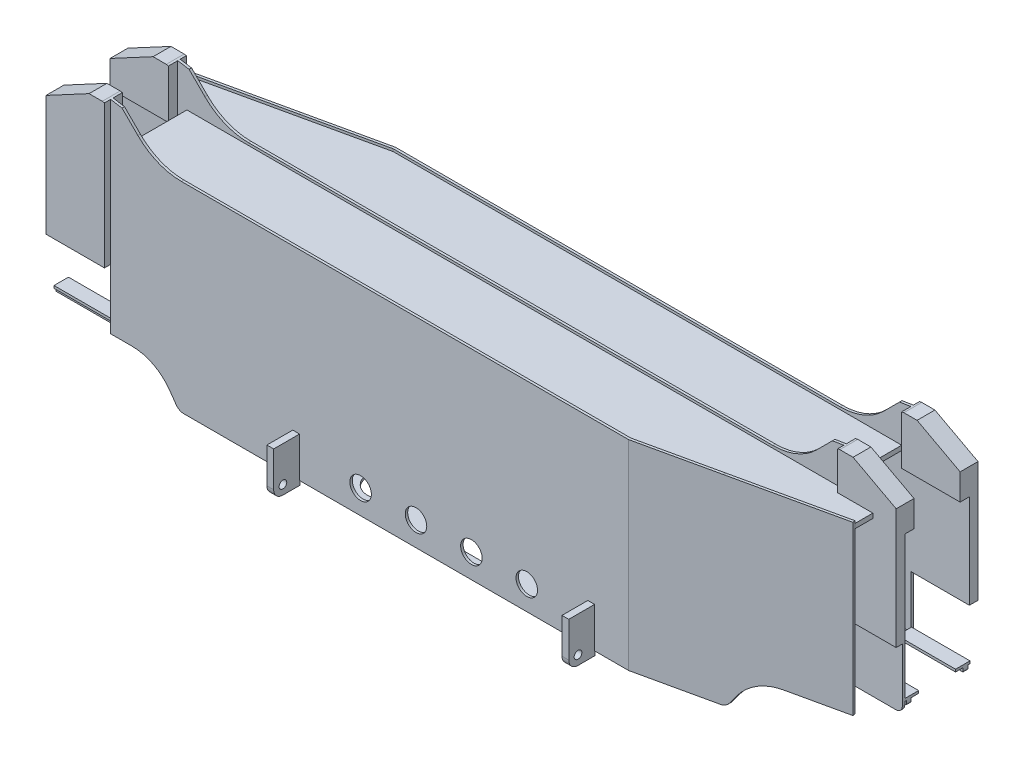
SolidWorks part; units mm, degrees
ref_plane "正面" through (0, 0, 0) normal (0, 0, 1) x (1, 0, 0)
ref_plane "平面" through (0, 0, 0) normal (0, 1, 0) x (1, 0, 0)
ref_plane "右側面" through (0, 0, 0) normal (1, 0, 0) x (0, 0, -1)
ref_plane "平面1" through (0, 0, 238) normal (0, 0, 1) x (1, 0, 0)
sketch "ｽｹｯﾁ2" plane through (0, 0, 238) normal (0, 0, 1) x (1, 0, 0)
  line L0 (20, 120) -> (259.781, 119.9998)
  line L1 (382.7741, 55.8641) -> (403.0452, 26.8271)
  line L2 (427.644, 13.9998) -> (2117.356, 13.9998)
  line L3 (2141.9548, 26.8271) -> (2162.2259, 55.8641)
  line L4 (2285.219, 119.9998) -> (2525, 120)
  line L5 (2545, 140) -> (2545, 315.36)
  line L6 (2545, 315.36) -> (2545, 706)
  line L7 (2545, 706) -> (2405, 781)
  line L8 (2405, 781) -> (2362, 781)
  line L9 (2362, 781) -> (2318, 774)
  line L10 (2318, 774) -> (2266.5789, 722.5791)
  line L11 (2125.157, 663.9999) -> (419.843, 663.9999)
  line L12 (278.4211, 722.5791) -> (227, 774)
  line L13 (227, 774) -> (183, 781)
  line L14 (183, 781) -> (140, 781)
  line L15 (140, 781) -> (0, 706)
  line L16 (0, 706) -> (0, 315.36)
  line L17 (0, 315.36) -> (0, 140)
  arc A0 (0, 140) -> (20, 120) centre (20, 140) ccw
  arc A1 (259.781, 119.9998) -> (382.7741, 55.8641) centre (259.781, -30) cw
  arc A2 (403.0452, 26.8271) -> (427.644, 13.9998) centre (427.644, 44) ccw
  arc A3 (2117.356, 13.9998) -> (2141.9548, 26.8271) centre (2117.356, 44) ccw
  arc A4 (2162.2259, 55.8641) -> (2285.219, 119.9998) centre (2285.219, -30) cw
  arc A5 (2525, 120) -> (2545, 140) centre (2525, 140) ccw
  arc A6 (2266.5789, 722.5791) -> (2125.157, 663.9999) centre (2125.157, 864) cw
  arc A7 (419.843, 663.9999) -> (278.4211, 722.5791) centre (419.843, 864) cw
extrude "ﾎﾞｽ - 押し出し1" add sketch "ｽｹｯﾁ2" along normal blind 8
sketch "ｽｹｯﾁ3" plane through (0, 0, 238) normal (0, 0, 1) x (1, 0, 0)
  line L0 (1072.5, 297) -> (1472.5, 297)
  line L1 (1472.5, 497) -> (1072.5, 497)
  circle A0 centre (972.5, 92) radius 35
  circle A1 centre (1272.5, 92) radius 35
  circle A2 centre (1572.5, 92) radius 35
  arc A3 (1472.5, 297) -> (1572.5, 397) centre (1472.5, 397) ccw
  arc A4 (1572.5, 397) -> (1472.5, 497) centre (1472.5, 397) ccw
  arc A5 (1072.5, 497) -> (972.5, 397) centre (1072.5, 397) ccw
  arc A6 (972.5, 397) -> (1072.5, 297) centre (1072.5, 397) ccw
  circle A7 centre (50, 499) radius 20.25
  circle A8 centre (2495, 499) radius 20.25
  circle A9 centre (27, 401.5) radius 10.5
  circle A10 centre (2518, 401.5) radius 10.5
sketch "ｽｹｯﾁ4" plane through (0, 0, 238) normal (0, 0, 1) x (1, 0, 0)
  line L0 (1072.5, 297) -> (1472.5, 297)
  line L1 (1472.5, 497) -> (1072.5, 497)
  circle A0 centre (972.5, 92) radius 35
  circle A1 centre (1272.5, 92) radius 35
  circle A2 centre (1572.5, 92) radius 35
  arc A3 (1472.5, 297) -> (1572.5, 397) centre (1472.5, 397) ccw
  arc A4 (1572.5, 397) -> (1472.5, 497) centre (1472.5, 397) ccw
  arc A5 (1072.5, 497) -> (972.5, 397) centre (1072.5, 397) ccw
  arc A6 (972.5, 397) -> (1072.5, 297) centre (1072.5, 397) ccw
  circle A7 centre (50, 499) radius 20.25
  circle A8 centre (2495, 499) radius 20.25
  circle A9 centre (27, 401.5) radius 10.5
  circle A10 centre (2518, 401.5) radius 10.5
extrude "ｶｯﾄ - 押し出し2" cut sketch "ｽｹｯﾁ4" along normal blind 8
ref_plane "平面2" through (0, 0, 20) normal (0, 0, 1) x (1, 0, 0)
sketch "ｽｹｯﾁ6" plane through (0, 0, 20) normal (0, 0, 1) x (1, 0, 0)
  line L0 (672.5, 14) -> (2117.356, 13.9998)
  line L1 (2141.9548, 26.8271) -> (2162.2259, 55.8641)
  line L2 (2285.219, 119.9998) -> (2355, 120)
  line L3 (2355, 120) -> (2355, 779.8864)
  line L4 (2355, 779.8864) -> (2318, 774)
  line L5 (2318, 774) -> (2266.5789, 722.5791)
  line L6 (2125.157, 663.9999) -> (672.5, 664)
  line L7 (672.5, 664) -> (672.5, 14)
  arc A0 (2117.356, 13.9998) -> (2141.9548, 26.8271) centre (2117.356, 44) ccw
  arc A1 (2162.2259, 55.8641) -> (2285.219, 119.9998) centre (2285.219, -30) cw
  arc A2 (2266.5789, 722.5791) -> (2125.157, 663.9999) centre (2125.157, 864) cw
extrude "ﾎﾞｽ - 押し出し2" add sketch "ｽｹｯﾁ6" along normal blind 8
sketch "ｽｹｯﾁ7" plane through (0, 0, 20) normal (0, 0, 1) x (1, 0, 0)
  circle A0 centre (1002.5, 92) radius 35
  circle A1 centre (1182.5, 92) radius 35
  circle A2 centre (1362.5, 92) radius 35
  circle A3 centre (1542.5, 92) radius 35
sketch "ｽｹｯﾁ8" plane through (0, 0, 20) normal (0, 0, 1) x (1, 0, 0)
  circle A0 centre (1002.5, 92) radius 35
  circle A1 centre (1182.5, 92) radius 35
  circle A2 centre (1362.5, 92) radius 35
  circle A3 centre (1542.5, 92) radius 35
extrude "ｶｯﾄ - 押し出し4" cut sketch "ｽｹｯﾁ8" along normal blind 8
ref_plane "平面3" through (0, 0, 456) normal (0, 0, 1) x (1, 0, 0)
sketch "ｽｹｯﾁ10" plane through (0, 0, 456) normal (0, 0, 1) x (1, 0, 0)
  line L0 (190, 120) -> (259.781, 119.9998)
  line L1 (382.7741, 55.8641) -> (403.0452, 26.8271)
  line L2 (427.644, 13.9998) -> (1872.5, 14)
  line L3 (1872.5, 14) -> (1872.5, 664)
  line L4 (1872.5, 664) -> (419.843, 663.9999)
  line L5 (278.4211, 722.5791) -> (227, 774)
  line L6 (227, 774) -> (190, 779.8864)
  line L7 (190, 779.8864) -> (190, 120)
  arc A0 (259.781, 119.9998) -> (382.7741, 55.8641) centre (259.781, -30) cw
  arc A1 (403.0452, 26.8271) -> (427.644, 13.9998) centre (427.644, 44) ccw
  arc A2 (419.843, 663.9999) -> (278.4211, 722.5791) centre (419.843, 864) cw
extrude "ﾎﾞｽ - 押し出し3" add sketch "ｽｹｯﾁ10" along normal blind 8
sketch "ｽｹｯﾁ11" plane through (0, 0, 456) normal (0, 0, 1) x (1, 0, 0)
  circle A0 centre (1002.5, 92) radius 35
  circle A1 centre (1182.5, 92) radius 35
  circle A2 centre (1362.5, 92) radius 35
  circle A3 centre (1542.5, 92) radius 35
sketch "ｽｹｯﾁ12" plane through (0, 0, 456) normal (0, 0, 1) x (1, 0, 0)
  circle A0 centre (1002.5, 92) radius 35
  circle A1 centre (1182.5, 92) radius 35
  circle A2 centre (1362.5, 92) radius 35
  circle A3 centre (1542.5, 92) radius 35
extrude "ｶｯﾄ - 押し出し6" cut sketch "ｽｹｯﾁ12" along normal blind 8
ref_plane "平面4" through (0, 14, 0) normal (0, 1, 0) x (1, 0, 0)
sketch "ｽｹｯﾁ14" plane through (0, 14, 0) normal (0, 1, 0) x (1, 0, 0)
  line L0 (678.3594, -26.7085) -> (75.7, -159.54)
  line L1 (75.7, -159.54) -> (73.9781, -151.7275)
  line L2 (73.9781, -151.7275) -> (671.6288, -20)
  line L3 (671.6288, -20) -> (676.8807, -20)
  line L4 (676.8807, -20) -> (678.3594, -26.7085)
extrude "ﾎﾞｽ - 押し出し4" add sketch "ｽｹｯﾁ14" along normal blind 650
sketch "ｽｹｯﾁ15" plane through (0, 14, 0) normal (0, 1, 0) x (1, 0, 0)
  line L0 (1866.6406, -457.2915) -> (2469.3, -324.46)
  line L1 (2469.3, -324.46) -> (2471.0219, -332.2725)
  line L2 (2471.0219, -332.2725) -> (1873.3712, -464)
  line L3 (1873.3712, -464) -> (1868.1193, -464)
  line L4 (1868.1193, -464) -> (1866.6406, -457.2915)
extrude "ﾎﾞｽ - 押し出し5" add sketch "ｽｹｯﾁ15" along normal blind 650
ref_plane "平面5" through (0, 641, 0) normal (0, 1, 0) x (1, 0, 0)
sketch "ｽｹｯﾁ17" plane through (0, 641, 0) normal (0, 1, 0) x (1, 0, 0)
  line L0 (2325, -28) -> (672.5, -28)
  line L1 (672.5, -28) -> (75.7, -159.54)
  line L2 (75.7, -159.54) -> (75.7, -238)
  line L3 (75.7, -238) -> (2325, -238)
  line L4 (2325, -238) -> (2325, -28)
extrude "ﾎﾞｽ - 押し出し6" add sketch "ｽｹｯﾁ17" along normal blind 15
sketch "ｽｹｯﾁ18" plane through (0, 641, 0) normal (0, 1, 0) x (1, 0, 0)
  line L0 (220, -246) -> (2469.3, -246)
  line L1 (2469.3, -246) -> (2469.3, -324.46)
  line L2 (2469.3, -324.46) -> (1872.5, -456)
  line L3 (1872.5, -456) -> (220, -456)
  line L4 (220, -456) -> (220, -246)
extrude "ﾎﾞｽ - 押し出し7" add sketch "ｽｹｯﾁ18" along normal blind 15
ref_plane "平面6" through (0, 22, 0) normal (0, 1, 0) x (1, 0, 0)
sketch "ｽｹｯﾁ20" plane through (0, 22, 0) normal (0, 1, 0) x (1, 0, 0)
  line L0 (804, -28) -> (2098.5, -28)
  line L1 (2098.5, -28) -> (2098.5, -238)
  line L2 (2098.5, -238) -> (804, -238)
  line L3 (804, -238) -> (804, -28)
extrude "ﾎﾞｽ - 押し出し8" add sketch "ｽｹｯﾁ20" along normal blind 8
sketch "ｽｹｯﾁ21" plane through (0, 22, 0) normal (0, 1, 0) x (1, 0, 0)
  line L0 (1202, -73) -> (1342, -73)
  line L1 (1342, -193) -> (1202, -193)
  circle A0 centre (972, -133) radius 60
  circle A1 centre (1572, -133) radius 60
  circle A2 centre (1942, -133) radius 60
  arc A3 (1342, -73) -> (1402, -133) centre (1342, -133) cw
  arc A4 (1402, -133) -> (1342, -193) centre (1342, -133) cw
  arc A5 (1202, -193) -> (1142, -133) centre (1202, -133) cw
  arc A6 (1142, -133) -> (1202, -73) centre (1202, -133) cw
sketch "ｽｹｯﾁ22" plane through (0, 22, 0) normal (0, 1, 0) x (1, 0, 0)
  line L0 (1202, -73) -> (1342, -73)
  line L1 (1342, -193) -> (1202, -193)
  circle A0 centre (972, -133) radius 60
  circle A1 centre (1572, -133) radius 60
  circle A2 centre (1942, -133) radius 60
  arc A3 (1342, -73) -> (1402, -133) centre (1342, -133) cw
  arc A4 (1402, -133) -> (1342, -193) centre (1342, -133) cw
  arc A5 (1202, -193) -> (1142, -133) centre (1202, -133) cw
  arc A6 (1142, -133) -> (1202, -73) centre (1202, -133) cw
extrude "ｶｯﾄ - 押し出し8" cut sketch "ｽｹｯﾁ22" along normal blind 8
sketch "ｽｹｯﾁ23" plane through (0, 22, 0) normal (0, 1, 0) x (1, 0, 0)
  line L0 (446.5, -246) -> (1741, -246)
  line L1 (1741, -246) -> (1741, -456)
  line L2 (1741, -456) -> (446.5, -456)
  line L3 (446.5, -456) -> (446.5, -246)
extrude "ﾎﾞｽ - 押し出し9" add sketch "ｽｹｯﾁ23" along normal blind 8
sketch "ｽｹｯﾁ24" plane through (0, 22, 0) normal (0, 1, 0) x (1, 0, 0)
  line L0 (1203, -291) -> (1343, -291)
  line L1 (1343, -411) -> (1203, -411)
  circle A0 centre (603, -351) radius 60
  circle A1 centre (973, -351) radius 60
  circle A2 centre (1573, -351) radius 60
  arc A3 (1343, -291) -> (1403, -351) centre (1343, -351) cw
  arc A4 (1403, -351) -> (1343, -411) centre (1343, -351) cw
  arc A5 (1203, -411) -> (1143, -351) centre (1203, -351) cw
  arc A6 (1143, -351) -> (1203, -291) centre (1203, -351) cw
extrude "ｶｯﾄ - 押し出し9" cut sketch "ｽｹｯﾁ24" along normal blind 8
ref_plane "平面7" through (0, 138, 0) normal (0, 1, 0) x (1, 0, 0)
sketch "ｽｹｯﾁ26" plane through (0, 138, 0) normal (0, 1, 0) x (1, 0, 0)
  line L0 (768, -28) -> (1712, -28)
  line L1 (1712, -28) -> (1712, -238)
  line L2 (1712, -238) -> (768, -238)
  line L3 (768, -238) -> (768, -28)
extrude "ﾎﾞｽ - 押し出し10" add sketch "ｽｹｯﾁ26" along normal blind 6
sketch "ｽｹｯﾁ27" plane through (0, 138, 0) normal (0, 1, 0) x (1, 0, 0)
  line L0 (833, -246) -> (1777, -246)
  line L1 (1777, -246) -> (1777, -456)
  line L2 (1777, -456) -> (833, -456)
  line L3 (833, -456) -> (833, -246)
extrude "ﾎﾞｽ - 押し出し11" add sketch "ｽｹｯﾁ27" along normal blind 6
ref_plane "平面8" through (0, 0, 218) normal (0, 0, 1) x (1, 0, 0)
sketch "ｽｹｯﾁ29" plane through (0, 0, 218) normal (0, 0, 1) x (1, 0, 0)
  line L0 (0, 315.36) -> (190, 315.36)
  line L1 (190, 315.36) -> (190, 779.8864)
  line L2 (190, 779.8864) -> (183, 781)
  line L3 (183, 781) -> (140, 781)
  line L4 (140, 781) -> (0, 706)
  line L5 (0, 706) -> (0, 315.36)
extrude "ﾎﾞｽ - 押し出し12" add sketch "ｽｹｯﾁ29" along normal blind 20
ref_plane "平面9" through (0, 0, 464) normal (0, 0, 1) x (1, 0, 0)
sketch "ｽｹｯﾁ31" plane through (0, 0, 464) normal (0, 0, 1) x (1, 0, 0)
  line L0 (0, 315.36) -> (190, 315.36)
  line L1 (190, 315.36) -> (190, 779.8864)
  line L2 (190, 779.8864) -> (183, 781)
  line L3 (183, 781) -> (140, 781)
  line L4 (140, 781) -> (0, 706)
  line L5 (0, 706) -> (0, 315.36)
extrude "ﾎﾞｽ - 押し出し13" add sketch "ｽｹｯﾁ31" along normal blind 20
sketch "ｽｹｯﾁ32" plane through (0, 0, 0) normal (0, 0, 1) x (1, 0, 0)
  line L0 (2545, 315.36) -> (2545, 706)
  line L1 (2545, 706) -> (2405, 781)
  line L2 (2405, 781) -> (2362, 781)
  line L3 (2362, 781) -> (2355, 779.8864)
  line L4 (2355, 779.8864) -> (2355, 315.36)
  line L5 (2355, 315.36) -> (2545, 315.36)
extrude "ﾎﾞｽ - 押し出し14" add sketch "ｽｹｯﾁ32" along normal blind 20
ref_plane "平面10" through (0, 0, 246) normal (0, 0, 1) x (1, 0, 0)
sketch "ｽｹｯﾁ34" plane through (0, 0, 246) normal (0, 0, 1) x (1, 0, 0)
  line L0 (2545, 315.36) -> (2545, 706)
  line L1 (2545, 706) -> (2405, 781)
  line L2 (2405, 781) -> (2362, 781)
  line L3 (2362, 781) -> (2355, 779.8864)
  line L4 (2355, 779.8864) -> (2355, 315.36)
  line L5 (2355, 315.36) -> (2545, 315.36)
extrude "ﾎﾞｽ - 押し出し15" add sketch "ｽｹｯﾁ34" along normal blind 20
sketch "ｽｹｯﾁ35" plane through (0, 0, 20) normal (0, 0, 1) x (1, 0, 0)
  line L0 (2545, 315.36) -> (2545, 706)
  line L1 (2545, 706) -> (2405, 781)
  line L2 (2405, 781) -> (2362, 781)
  line L3 (2362, 781) -> (2355, 779.8864)
  line L4 (2355, 779.8864) -> (2355, 315.36)
  line L5 (2355, 315.36) -> (2545, 315.36)
extrude "ﾎﾞｽ - 押し出し16" add sketch "ｽｹｯﾁ35" along normal blind 8
sketch "ｽｹｯﾁ36" plane through (0, 0, 456) normal (0, 0, 1) x (1, 0, 0)
  line L0 (0, 315.36) -> (190, 315.36)
  line L1 (190, 315.36) -> (190, 779.8864)
  line L2 (190, 779.8864) -> (183, 781)
  line L3 (183, 781) -> (140, 781)
  line L4 (140, 781) -> (0, 706)
  line L5 (0, 706) -> (0, 315.36)
extrude "ﾎﾞｽ - 押し出し17" add sketch "ｽｹｯﾁ36" along normal blind 8
sketch "ｽｹｯﾁ37" plane through (0, 0, 246) normal (0, 0, 1) x (1, 0, 0)
  line L0 (0, 620.82) -> (190, 620.82)
  line L1 (190, 620.82) -> (190, 779.8864)
  line L2 (190, 779.8864) -> (183, 781)
  line L3 (183, 781) -> (140, 781)
  line L4 (140, 781) -> (0, 706)
  line L5 (0, 706) -> (0, 620.82)
extrude "ﾎﾞｽ - 押し出し18" add sketch "ｽｹｯﾁ37" along normal blind 30
ref_plane "平面11" through (0, 0, 426) normal (0, 0, 1) x (1, 0, 0)
sketch "ｽｹｯﾁ39" plane through (0, 0, 426) normal (0, 0, 1) x (1, 0, 0)
  line L0 (0, 620.82) -> (190, 620.82)
  line L1 (190, 620.82) -> (190, 779.8864)
  line L2 (190, 779.8864) -> (183, 781)
  line L3 (183, 781) -> (140, 781)
  line L4 (140, 781) -> (0, 706)
  line L5 (0, 706) -> (0, 620.82)
extrude "ﾎﾞｽ - 押し出し19" add sketch "ｽｹｯﾁ39" along normal blind 30
ref_plane "平面12" through (0, 0, 28) normal (0, 0, 1) x (1, 0, 0)
sketch "ｽｹｯﾁ41" plane through (0, 0, 28) normal (0, 0, 1) x (1, 0, 0)
  line L0 (2545, 620.82) -> (2545, 706)
  line L1 (2545, 706) -> (2405, 781)
  line L2 (2405, 781) -> (2362, 781)
  line L3 (2362, 781) -> (2355, 779.8864)
  line L4 (2355, 779.8864) -> (2355, 620.82)
  line L5 (2355, 620.82) -> (2545, 620.82)
extrude "ﾎﾞｽ - 押し出し20" add sketch "ｽｹｯﾁ41" along normal blind 30
ref_plane "平面13" through (0, 0, 208) normal (0, 0, 1) x (1, 0, 0)
sketch "ｽｹｯﾁ43" plane through (0, 0, 208) normal (0, 0, 1) x (1, 0, 0)
  line L0 (2545, 620.82) -> (2545, 706)
  line L1 (2545, 706) -> (2405, 781)
  line L2 (2405, 781) -> (2362, 781)
  line L3 (2362, 781) -> (2355, 779.8864)
  line L4 (2355, 779.8864) -> (2355, 620.82)
  line L5 (2355, 620.82) -> (2545, 620.82)
extrude "ﾎﾞｽ - 押し出し21" add sketch "ｽｹｯﾁ43" along normal blind 30
sketch "ｽｹｯﾁ44" plane through (0, 138, 0) normal (0, 1, 0) x (1, 0, 0)
  line L0 (0, -251) -> (833, -251)
  line L1 (833, -251) -> (833, -451)
  line L2 (833, -451) -> (0, -451)
  line L3 (0, -451) -> (0, -251)
extrude "ﾎﾞｽ - 押し出し22" add sketch "ｽｹｯﾁ44" along normal blind 12
sketch "ｽｹｯﾁ45" plane through (0, 138, 0) normal (0, 1, 0) x (1, 0, 0)
  line L0 (-10, -267) -> (145.3, -267)
  line L1 (185.3, -307) -> (185.3, -395)
  line L2 (145.3, -435) -> (-10, -435)
  line L3 (-10, -435) -> (-10, -267)
  arc A0 (145.3, -267) -> (185.3, -307) centre (145.3, -307) cw
  arc A1 (185.3, -395) -> (145.3, -435) centre (145.3, -395) cw
sketch "ｽｹｯﾁ46" plane through (0, 138, 0) normal (0, 1, 0) x (1, 0, 0)
  line L0 (-10, -267) -> (145.3, -267)
  line L1 (185.3, -307) -> (185.3, -395)
  line L2 (145.3, -435) -> (-10, -435)
  line L3 (-10, -435) -> (-10, -267)
  arc A0 (145.3, -267) -> (185.3, -307) centre (145.3, -307) cw
  arc A1 (185.3, -395) -> (145.3, -435) centre (145.3, -395) cw
extrude "ｶｯﾄ - 押し出し11" cut sketch "ｽｹｯﾁ46" along normal blind 12
sketch "ｽｹｯﾁ47" plane through (0, 138, 0) normal (0, 1, 0) x (1, 0, 0)
  line L0 (1712, -33) -> (2545, -33)
  line L1 (2545, -33) -> (2545, -233)
  line L2 (2545, -233) -> (1712, -233)
  line L3 (1712, -233) -> (1712, -33)
extrude "ﾎﾞｽ - 押し出し23" add sketch "ｽｹｯﾁ47" along normal blind 12
sketch "ｽｹｯﾁ48" plane through (0, 138, 0) normal (0, 1, 0) x (1, 0, 0)
  line L0 (2555, -217) -> (2399.7, -217)
  line L1 (2359.7, -177) -> (2359.7, -89)
  line L2 (2399.7, -49) -> (2555, -49)
  line L3 (2555, -49) -> (2555, -217)
  arc A0 (2399.7, -217) -> (2359.7, -177) centre (2399.7, -177) cw
  arc A1 (2359.7, -89) -> (2399.7, -49) centre (2399.7, -89) cw
extrude "ｶｯﾄ - 押し出し12" cut sketch "ｽｹｯﾁ48" along normal blind 12
ref_plane "平面14" through (0, 150, 0) normal (0, 1, 0) x (1, 0, 0)
sketch "ｽｹｯﾁ50" plane through (0, 150, 0) normal (0, 1, 0) x (1, 0, 0)
  line L0 (0, -244) -> (190, -244)
  line L1 (190, -244) -> (190, -291)
  line L2 (190, -291) -> (0, -291)
  line L3 (0, -291) -> (0, -244)
  line L4 (0, -411) -> (190, -411)
  line L5 (190, -411) -> (190, -458)
  line L6 (190, -458) -> (0, -458)
  line L7 (0, -458) -> (0, -411)
  line L8 (215.708, -244) -> (833, -244)
  line L9 (833, -244) -> (833, -291)
  line L10 (833, -291) -> (215.708, -291)
  line L11 (215.708, -291) -> (215.708, -244)
  line L12 (215.708, -411) -> (833, -411)
  line L13 (833, -411) -> (833, -458)
  line L14 (833, -458) -> (215.708, -458)
  line L15 (215.708, -458) -> (215.708, -411)
extrude "ﾎﾞｽ - 押し出し24" add sketch "ｽｹｯﾁ50" along normal blind 8
sketch "ｽｹｯﾁ51" plane through (0, 150, 0) normal (0, 1, 0) x (1, 0, 0)
  line L0 (1712, -193) -> (2329.292, -193)
  line L1 (2329.292, -193) -> (2329.292, -240)
  line L2 (2329.292, -240) -> (1712, -240)
  line L3 (1712, -240) -> (1712, -193)
  line L4 (1712, -26) -> (2329.292, -26)
  line L5 (2329.292, -26) -> (2329.292, -73)
  line L6 (2329.292, -73) -> (1712, -73)
  line L7 (1712, -73) -> (1712, -26)
  line L8 (2355, -193) -> (2545, -193)
  line L9 (2545, -193) -> (2545, -240)
  line L10 (2545, -240) -> (2355, -240)
  line L11 (2355, -240) -> (2355, -193)
  line L12 (2355, -26) -> (2545, -26)
  line L13 (2545, -26) -> (2545, -73)
  line L14 (2545, -73) -> (2355, -73)
  line L15 (2355, -73) -> (2355, -26)
extrude "ﾎﾞｽ - 押し出し25" add sketch "ｽｹｯﾁ51" along normal blind 8
ref_plane "平面15" through (1771.5, 0, 0) normal (1, 0, 0) x (0, 0, -1)
sketch "ｽｹｯﾁ53" plane through (1771.5, 0, 0) normal (1, 0, 0) x (0, 0, -1)
  line L0 (-28, 30) -> (-40.32, 29.97)
  line L1 (-40.32, 29.97) -> (-63.75, 129.12)
  line L2 (-63.75, 129.12) -> (-53.54, 138)
  line L3 (-53.54, 138) -> (-28, 30)
extrude "ﾎﾞｽ - 押し出し27" add sketch "ｽｹｯﾁ53" along normal blind 319 separate body
sketch "ｽｹｯﾁ54" plane through (1771.5, 0, 0) normal (1, 0, 0) x (0, 0, -1)
  line L0 (-212.46, 138) -> (-202.25, 129.12)
  line L1 (-202.25, 129.12) -> (-225.68, 29.97)
  line L2 (-225.68, 29.97) -> (-238, 30)
  line L3 (-238, 30) -> (-212.46, 138)
extrude "ﾎﾞｽ - 押し出し29" add sketch "ｽｹｯﾁ54" along normal blind 319 separate body
ref_plane "平面16" through (454.5, 0, 0) normal (1, 0, 0) x (0, 0, -1)
sketch "ｽｹｯﾁ56" plane through (454.5, 0, 0) normal (1, 0, 0) x (0, 0, -1)
  line L0 (-430.46, 138) -> (-420.25, 129.12)
  line L1 (-420.25, 129.12) -> (-443.68, 29.97)
  line L2 (-443.68, 29.97) -> (-456, 30)
  line L3 (-456, 30) -> (-430.46, 138)
extrude "ﾎﾞｽ - 押し出し31" add sketch "ｽｹｯﾁ56" along normal blind 319 separate body
sketch "ｽｹｯﾁ57" plane through (454.5, 0, 0) normal (1, 0, 0) x (0, 0, -1)
  line L0 (-246, 30) -> (-258.32, 29.97)
  line L1 (-258.32, 29.97) -> (-281.75, 129.12)
  line L2 (-281.75, 129.12) -> (-271.54, 138)
  line L3 (-271.54, 138) -> (-246, 30)
extrude "ﾎﾞｽ - 押し出し33" add sketch "ｽｹｯﾁ57" along normal blind 319 separate body
sketch "ｽｹｯﾁ58" plane through (0, 0, 0) normal (0, 0, 1) x (1, 0, 0)
  line L0 (-80, -80) -> (2625, -80)
  line L1 (2625, -80) -> (2625, 860)
  line L2 (2625, 860) -> (-80, 860)
  line L3 (-80, 860) -> (-80, -80)
  line L4 (20, 120) -> (259.781, 119.9998)
  line L5 (382.7741, 55.8641) -> (403.0452, 26.8271)
  line L6 (427.644, 13.9998) -> (2117.356, 13.9998)
  line L7 (2141.9548, 26.8271) -> (2162.2259, 55.8641)
  line L8 (2285.219, 119.9998) -> (2525, 120)
  line L9 (2545, 140) -> (2545, 315.36)
  line L10 (2545, 315.36) -> (2545, 706)
  line L11 (2545, 706) -> (2405, 781)
  line L12 (2405, 781) -> (2362, 781)
  line L13 (2362, 781) -> (2318, 774)
  line L14 (2318, 774) -> (2266.5789, 722.5791)
  line L15 (2125.157, 663.9999) -> (419.843, 663.9999)
  line L16 (278.4211, 722.5791) -> (227, 774)
  line L17 (227, 774) -> (183, 781)
  line L18 (183, 781) -> (140, 781)
  line L19 (140, 781) -> (0, 706)
  line L20 (0, 706) -> (0, 315.36)
  line L21 (0, 315.36) -> (0, 140)
  arc A0 (0, 140) -> (20, 120) centre (20, 140) ccw
  arc A1 (259.781, 119.9998) -> (382.7741, 55.8641) centre (259.781, -30) cw
  arc A2 (403.0452, 26.8271) -> (427.644, 13.9998) centre (427.644, 44) ccw
  arc A3 (2117.356, 13.9998) -> (2141.9548, 26.8271) centre (2117.356, 44) ccw
  arc A4 (2162.2259, 55.8641) -> (2285.219, 119.9998) centre (2285.219, -30) cw
  arc A5 (2525, 120) -> (2545, 140) centre (2525, 140) ccw
  arc A6 (2266.5789, 722.5791) -> (2125.157, 663.9999) centre (2125.157, 864) cw
  arc A7 (419.843, 663.9999) -> (278.4211, 722.5791) centre (419.843, 864) cw
sketch "ｽｹｯﾁ59" plane through (0, 0, 0) normal (0, 0, 1) x (1, 0, 0)
  line L0 (-80, -80) -> (2625, -80)
  line L1 (2625, -80) -> (2625, 860)
  line L2 (2625, 860) -> (-80, 860)
  line L3 (-80, 860) -> (-80, -80)
  line L4 (20, 120) -> (259.781, 119.9998)
  line L5 (382.7741, 55.8641) -> (403.0452, 26.8271)
  line L6 (427.644, 13.9998) -> (2117.356, 13.9998)
  line L7 (2141.9548, 26.8271) -> (2162.2259, 55.8641)
  line L8 (2285.219, 119.9998) -> (2525, 120)
  line L9 (2545, 140) -> (2545, 315.36)
  line L10 (2545, 315.36) -> (2545, 706)
  line L11 (2545, 706) -> (2405, 781)
  line L12 (2405, 781) -> (2362, 781)
  line L13 (2362, 781) -> (2318, 774)
  line L14 (2318, 774) -> (2266.5789, 722.5791)
  line L15 (2125.157, 663.9999) -> (419.843, 663.9999)
  line L16 (278.4211, 722.5791) -> (227, 774)
  line L17 (227, 774) -> (183, 781)
  line L18 (183, 781) -> (140, 781)
  line L19 (140, 781) -> (0, 706)
  line L20 (0, 706) -> (0, 315.36)
  line L21 (0, 315.36) -> (0, 140)
  arc A0 (0, 140) -> (20, 120) centre (20, 140) ccw
  arc A1 (259.781, 119.9998) -> (382.7741, 55.8641) centre (259.781, -30) cw
  arc A2 (403.0452, 26.8271) -> (427.644, 13.9998) centre (427.644, 44) ccw
  arc A3 (2117.356, 13.9998) -> (2141.9548, 26.8271) centre (2117.356, 44) ccw
  arc A4 (2162.2259, 55.8641) -> (2285.219, 119.9998) centre (2285.219, -30) cw
  arc A5 (2525, 120) -> (2545, 140) centre (2525, 140) ccw
  arc A6 (2266.5789, 722.5791) -> (2125.157, 663.9999) centre (2125.157, 864) cw
  arc A7 (419.843, 663.9999) -> (278.4211, 722.5791) centre (419.843, 864) cw
extrude "ｶｯﾄ - 押し出し14" cut sketch "ｽｹｯﾁ59" along normal blind 600
ref_plane "平面17" through (782, 0, 0) normal (1, 0, 0) x (0, 0, -1)
sketch "ｽｹｯﾁ61" plane through (782, 0, 0) normal (1, 0, 0) x (0, 0, -1)
  line L0 (-26, 29) -> (-240, 29)
  line L1 (-240, 29) -> (-240, 138)
  line L2 (-240, 138) -> (-26, 138)
  line L3 (-26, 138) -> (-26, 29)
  line L4 (-244, 29) -> (-458, 29)
  line L5 (-458, 29) -> (-458, 138)
  line L6 (-458, 138) -> (-244, 138)
  line L7 (-244, 138) -> (-244, 29)
  line L8 (-462, 0) -> (-518, 0)
  line L9 (-548, 30) -> (-548, 145)
  line L10 (-548, 145) -> (-462, 145)
  line L11 (-462, 145) -> (-462, 0)
  arc A0 (-518, 0) -> (-548, 30) centre (-518, 30) cw
extrude "ﾎﾞｽ - 押し出し34" add sketch "ｽｹｯﾁ61" along normal blind 22
sketch "ｽｹｯﾁ62" plane through (782, 0, 0) normal (1, 0, 0) x (0, 0, -1)
  circle A0 centre (-518, 30) radius 12.5
sketch "ｽｹｯﾁ63" plane through (782, 0, 0) normal (1, 0, 0) x (0, 0, -1)
  circle A0 centre (-518, 30) radius 12.5
extrude "ｶｯﾄ - 押し出し16" cut sketch "ｽｹｯﾁ63" along normal blind 22
ref_plane "平面18" through (1741, 0, 0) normal (1, 0, 0) x (0, 0, -1)
sketch "ｽｹｯﾁ65" plane through (1741, 0, 0) normal (1, 0, 0) x (0, 0, -1)
  line L0 (-26, 29) -> (-240, 29)
  line L1 (-240, 29) -> (-240, 138)
  line L2 (-240, 138) -> (-26, 138)
  line L3 (-26, 138) -> (-26, 29)
  line L4 (-244, 29) -> (-458, 29)
  line L5 (-458, 29) -> (-458, 138)
  line L6 (-458, 138) -> (-244, 138)
  line L7 (-244, 138) -> (-244, 29)
  line L8 (-462, 0) -> (-518, 0)
  line L9 (-548, 30) -> (-548, 145)
  line L10 (-548, 145) -> (-462, 145)
  line L11 (-462, 145) -> (-462, 0)
  arc A0 (-518, 0) -> (-548, 30) centre (-518, 30) cw
extrude "ﾎﾞｽ - 押し出し35" add sketch "ｽｹｯﾁ65" along normal blind 22
sketch "ｽｹｯﾁ66" plane through (1741, 0, 0) normal (1, 0, 0) x (0, 0, -1)
  circle A0 centre (-518, 30) radius 12.5
sketch "ｽｹｯﾁ67" plane through (1741, 0, 0) normal (1, 0, 0) x (0, 0, -1)
  circle A0 centre (-518, 30) radius 12.5
extrude "ｶｯﾄ - 押し出し18" cut sketch "ｽｹｯﾁ67" along normal blind 22
